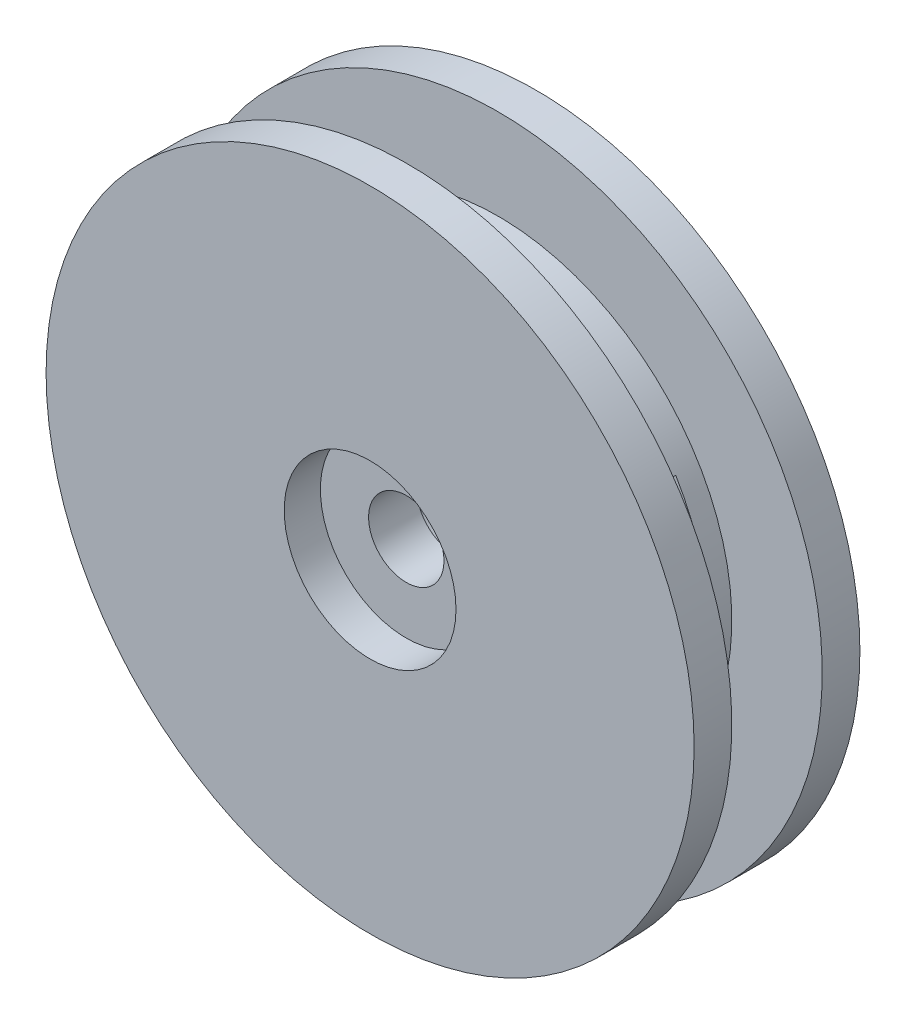
SolidWorks part; units mm, degrees
ref_plane "Alzado" through (0, 0, 0) normal (0, 0, 1) x (1, 0, 0)
ref_plane "Planta" through (0, 0, 0) normal (0, 1, 0) x (1, 0, 0)
ref_plane "Vista lateral" through (0, 0, 0) normal (1, 0, 0) x (0, 0, -1)
sketch "Croquis1" plane through (0, 0, 0) normal (0, 0, 1) x (1, 0, 0)
  circle A0 centre (0, 0) radius 10.75
  dimension "D1" = 21.5
extrude "Saliente-Extruir1" add sketch "Croquis1" along normal blind 5.5
sketch "Croquis2" plane through (0, 0, 0) normal (1, 0, 0) x (0, 0, -1)
  line L0 (0, 10.75) -> (-5.5, 10.75) construction
  line L1 (0, 10.75) -> (-5.5, 10.75) construction
  line L2 (-5.5, 10.75) -> (-4.25, 10.75)
  line L3 (-4.25, 10.75) -> (-4.25, 7.75)
  line L4 (-4.25, 7.75) -> (-1.25, 7.75)
  line L5 (-1.25, 7.75) -> (-1.25, 10.75)
  line L6 (-1.25, 10.75) -> (0, 10.75)
  line L7 (-2.75, 10.75) -> (-2.75, 7.75) construction
  line L8 (0, 0) -> (-5.5, 0) construction
  line L9 (-5.5, 10.75) -> (-5.5, -10.75) construction
  line L10 (-5.5, 10.75) -> (-5.5, 13.5306)
  line L11 (-5.5, 13.5306) -> (0, 13.5306)
  line L12 (0, 13.5306) -> (0, 10.75)
  point P8 (-2.75, 7.75)
  dimension "D1" = 3
  dimension "D2" = 3
revolve "Cortar-Revolución1" cut sketch "Croquis2" angle 360 about L8
sketch "Croquis3" plane through (0, 0, 5.5) normal (0, 0, 1) x (1, 0, 0)
  circle A0 centre (0, 0) radius 2.85
  dimension "D1" = 5.7
extrude "Cortar-Extruir1" cut sketch "Croquis3" against normal blind 1.2
sketch "Croquis4" plane through (0, 0, 5.5) normal (0, 0, 1) x (1, 0, 0)
  circle A0 centre (0, 0) radius 1.25
  dimension "D1" = 2.5
extrude "Cortar-Extruir2" cut sketch "Croquis4" against normal through all
sketch "Croquis5" plane through (0, 0, 0) normal (0, 0, -1) x (-1, 0, 0)
  circle A0 centre (0, 0) radius 2.32
  dimension "D1" = 4.64
extrude "Cortar-Extruir3" cut sketch "Croquis5" against normal blind 2.7
sketch "Croquis6" plane through (0, 0, 0) normal (1, 0, 0) x (0, 0, -1)
  line L0 (0, 0) -> (-2.75, 0) construction
  line L1 (-2.75, 0) -> (-2.75, 7.75) construction
  line L2 (-1.25, 7.75) -> (-4.25, 7.75) construction
  line L4 (-3.5, 2.5) -> (-2, 2.5)
  line L5 (-3.5, 2.5) -> (-3.5, 4)
  line L6 (-3.5, 4) -> (-2, 4)
  line L7 (-2, 2.5) -> (-2, 4)
  line L8 (-3.5, 2.5) -> (-2, 4) construction
  line L9 (-3.5, 4) -> (-2, 2.5) construction
  point P6 (-2.75, 3.25)
  dimension "D1" = 1.5
  dimension "D2" = 2.5
extrude "Cortar-Extruir4" cut sketch "Croquis6" against normal through all both and the other way through all
